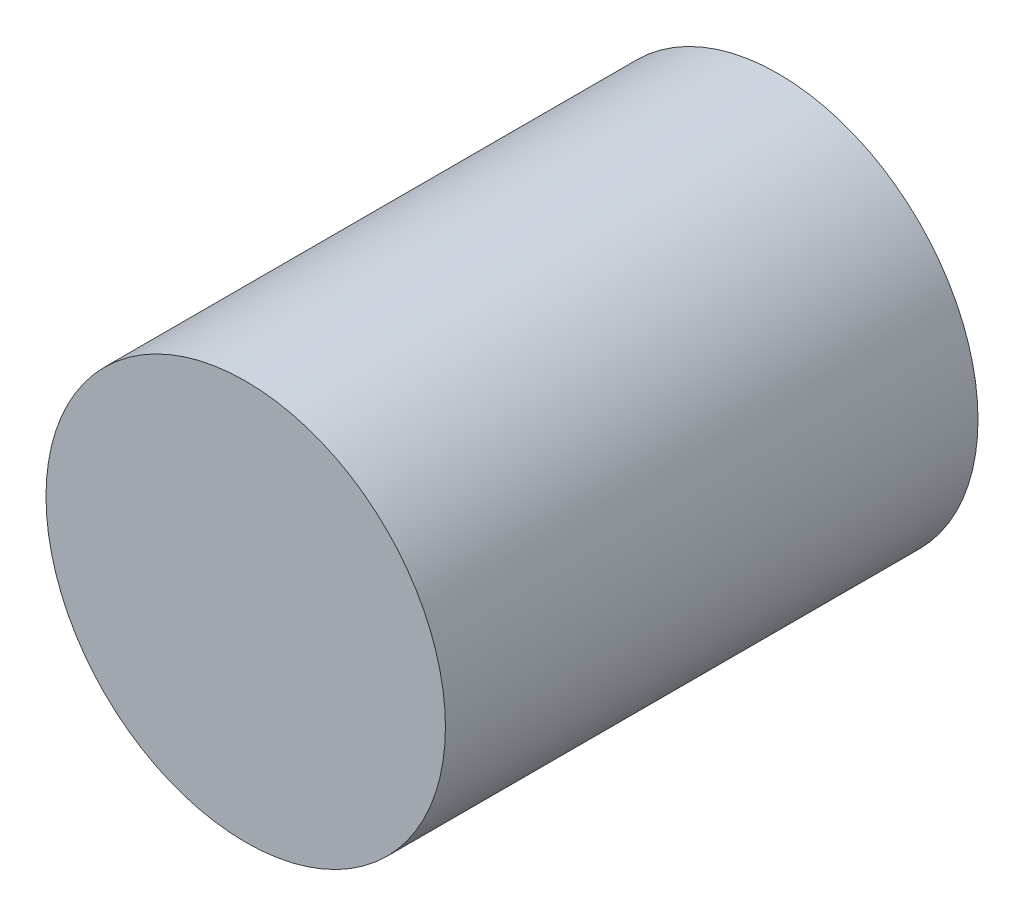
SolidWorks part; units mm, degrees
material "PET"
ref_plane "Front Plane" through (0, 0, 0) normal (0, 0, 1) x (1, 0, 0)
ref_plane "Top Plane" through (0, 0, 0) normal (0, 1, 0) x (1, 0, 0)
ref_plane "Right Plane" through (0, 0, 0) normal (1, 0, 0) x (0, 0, -1)
sketch "Sketch1" plane through (0, 0, 0) normal (0, 0, 1) x (1, 0, 0)
  line L0 (0, 0) -> (2.0103, 0)
  line L1 (2.0103, 0) -> (2.0103, 10)
  line L2 (2.0103, 10) -> (-2, 10)
  line L3 (-2, 10) -> (-2, 0)
  line L4 (-2, 0) -> (0, 0)
  circle A0 centre (0, 0) radius 6.3
  circle A1 centre (0, 0) radius 15
  dimension "D1" = 12.6
  dimension "D2" = 30
  dimension "D3" = 10
  dimension "D4" = 2.0103
  dimension "D5" = 2
  dimension "D6" = 4.0103
extrude "Boss-Extrude1" add sketch "Sketch1" along normal blind 40 contours A1 A0 L3 L2 L1
sketch "Sketch2" plane through (0, 0, 40) normal (0, 0, 1) x (1, 0, 0)
  circle A0 centre (0, 0) radius 15
extrude "Boss-Extrude2" add sketch "Sketch2" against normal blind 20
